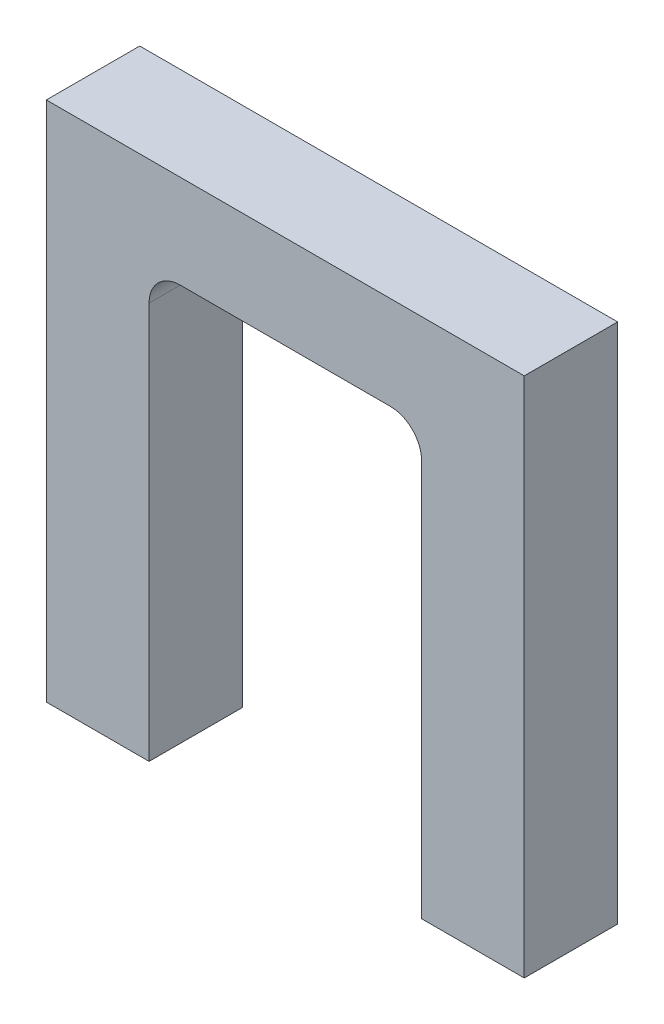
SolidWorks part; units mm, degrees
ref_plane "Front" through (0, 0, 0) normal (0, 0, 1) x (1, 0, 0)
ref_plane "Top" through (0, 0, 0) normal (0, 1, 0) x (1, 0, 0)
ref_plane "Right" through (0, 0, 0) normal (1, 0, 0) x (0, 0, -1)
sketch "Sketch1" plane through (0, 0, 0) normal (0, 0, 1) x (1, 0, 0)
  line L1 (-15.35, -7.0937) -> (-15.35, 26.4063)
  line L2 (-15.35, 26.4063) -> (-15.4511, 26.4063)
  line L7 (-8.75, 18.4063) -> (-8.75, -7.0937)
  line L8 (-8.75, -7.0937) -> (-15.35, -7.0937)
  line L9 (0, 33.1823) -> (0, -10.1823) construction
  line L10 (8.75, -7.0937) -> (15.35, -7.0937)
  line L13 (15.35, 26.4063) -> (15.4511, 26.4063)
  line L14 (15.35, -7.0937) -> (15.35, 26.4063)
  line L15 (-12.05, 28.4002) -> (-12.05, -6.2121) construction
  line L16 (-15.35, 26.4063) -> (15.35, 26.4063)
  line L17 (-6.75, 20.4063) -> (6.75, 20.4063)
  line L18 (12.05, 28.4002) -> (12.05, -6.2121) construction
  line L19 (8.75, 18.4063) -> (8.75, -7.0937)
  arc A0 (-6.75, 20.4063) -> (-8.75, 18.4063) centre (-6.75, 18.4063) ccw
  arc A1 (6.75, 20.4063) -> (8.75, 18.4063) centre (6.75, 18.4063) cw
  point P2 (0, 26.4063)
  point P11 (0, 24.299)
  point P12 (0, 20.4063)
  point P20 (-8.75, 19.4063)
  point P26 (8.75, 19.4063)
  point P27 (0, 20.4063)
  dimension "D5" = 2
  dimension "D1" = 17.5
  dimension "D2" = 3.3
  dimension "D3" = 6.6
  dimension "D4" = 26.5
  dimension "D6" = 6
extrude "Boss-Extrude1" add sketch "Sketch1" along normal mid plane 6 contours L17 A1 L19 L10 L14 L16 L1 L8 L7 A0
sketch "Sketch2" plane through (0, -7.0937, 0) normal (0, -1, 0) x (1, 0, 0)
  line L0 (-8.75, 3) -> (-15.35, 3) construction
  line L1 (0, 6.9191) -> (0, -6.4476) construction
  circle A0 centre (-12.05, 0) radius 1.5
  circle A2 centre (12.05, 0) radius 1.5
  point P6 (-12.05, 3)
  dimension "D1" = 3
extrude "Cut-Extrude1" cut sketch "Sketch2" against normal blind 12
